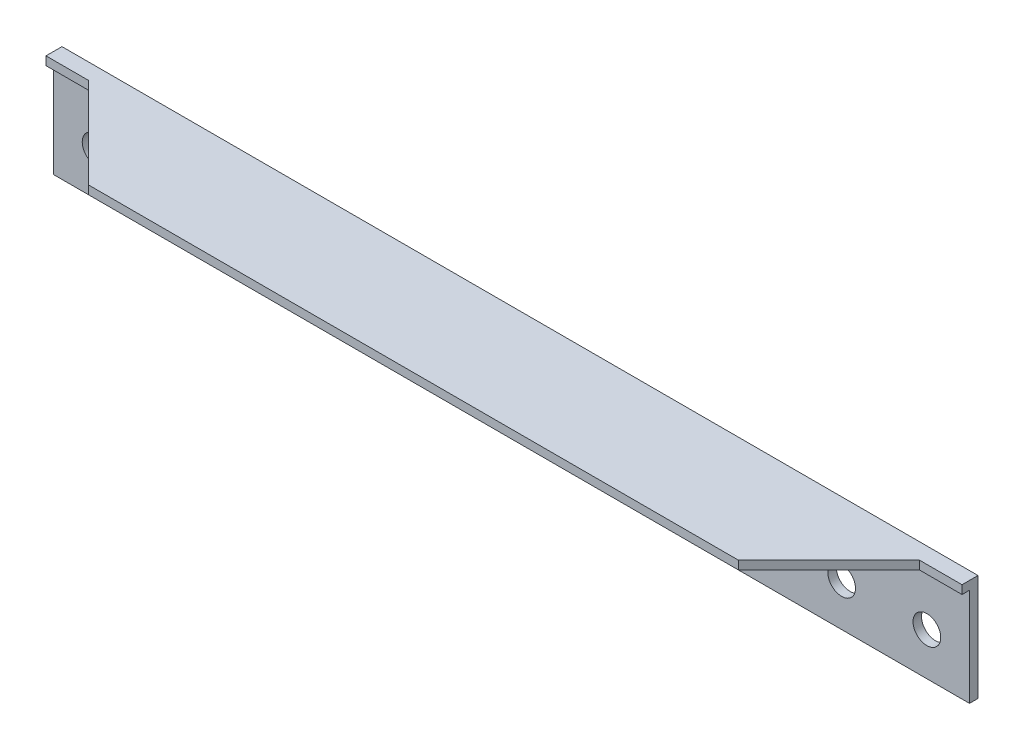
SolidWorks part; units mm, degrees
ref_plane "前视基准面" through (0, 0, 0) normal (0, 0, 1) x (1, 0, 0)
ref_plane "上视基准面" through (0, 0, 0) normal (0, 1, 0) x (1, 0, 0)
ref_plane "右视基准面" through (0, 0, 0) normal (1, 0, 0) x (0, 0, -1)
sketch "草图1" plane through (0, 0, 0) normal (0, 0, 1) x (1, 0, 0)
  line L0 (-1000, 0) -> (49000, 0) construction
  line L1 (-430, 0) -> (430, 0)
  line L2 (430, 0) -> (430, 100)
  line L3 (430, 100) -> (-430, 100)
  line L4 (0, -1000) -> (0, 49000) construction
  line L5 (390, -944.3218) -> (390, 49055.6782) construction
  line L6 (-723.7245, 40) -> (49276.2755, 40) construction
  line L7 (310, -974.291) -> (310, 49025.709) construction
  line L8 (-430, 0) -> (-430, 100)
  circle A0 centre (390, 40) radius 13
  circle A1 centre (310, 40) radius 13
  circle A2 centre (-390, 40) radius 13
  circle A3 centre (-310, 40) radius 13
  point P12 (390, 40)
  point P17 (310, 40)
  point P26 (0, 0)
  point P27 (0, 100)
  dimension "D6" = 26
  dimension "D8" = 26
  dimension "D1" = 430
  dimension "D2" = 100
  dimension "D4" = 40
  dimension "D5" = 60
  dimension "D7" = 80
extrude "凸台-拉伸1" add sketch "草图1" along normal blind 8
sketch "草图2" plane through (0, 0, 8) normal (0, 0, 1) x (1, 0, 0)
  line L1 (-430, 100) -> (430, 100)
  line L2 (-430, 100) -> (-430, 92)
  line L3 (-430, 92) -> (430, 92)
  line L4 (430, 100) -> (430, 92)
  point P0 (-430, 100)
  dimension "D1" = 860
  dimension "D2" = 8
extrude "凸台-拉伸2" add sketch "草图2" along normal blind 92
sketch "草图3" plane through (0, 100, 0) normal (0, 1, 0) x (1, 0, 0)
  line L0 (-390, -1024.4681) -> (-390, 48975.5319) construction
  line L1 (-430, -100) -> (-430, 0) construction
  dimension "D1" = 40
sketch "草图4" plane through (0, 100, 0) normal (0, 1, 0) x (1, 0, 0)
  line L0 (-1254.233, -15) -> (48745.767, -15) construction
  line L1 (430, 0) -> (-430, 0) construction
  line L2 (-390, -201024.4681) -> (-390, 248975.5319) construction
  line L3 (-390, -15) -> (34965.3391, -35370.3391) construction
  line L4 (430, -100) -> (-430, -100) construction
  line L5 (-430, -100) -> (-430, 0) construction
  line L6 (-430, -15) -> (-390, -15)
  line L7 (-390, -15) -> (-305, -100)
  line L8 (-305, -100) -> (-430, -100)
  line L9 (-430, -100) -> (-430, -15)
  point P4 (-390, -15)
  point P9 (-305, -100)
  point P10 (-430, -15)
  dimension "D1" = 15
  dimension "D2" = 45
extrude "切除-拉伸1" cut sketch "草图4" against normal through all
mirror "镜向1" about plane through (0, 0, 0) normal (1, 0, 0) of "切除-拉伸1"
